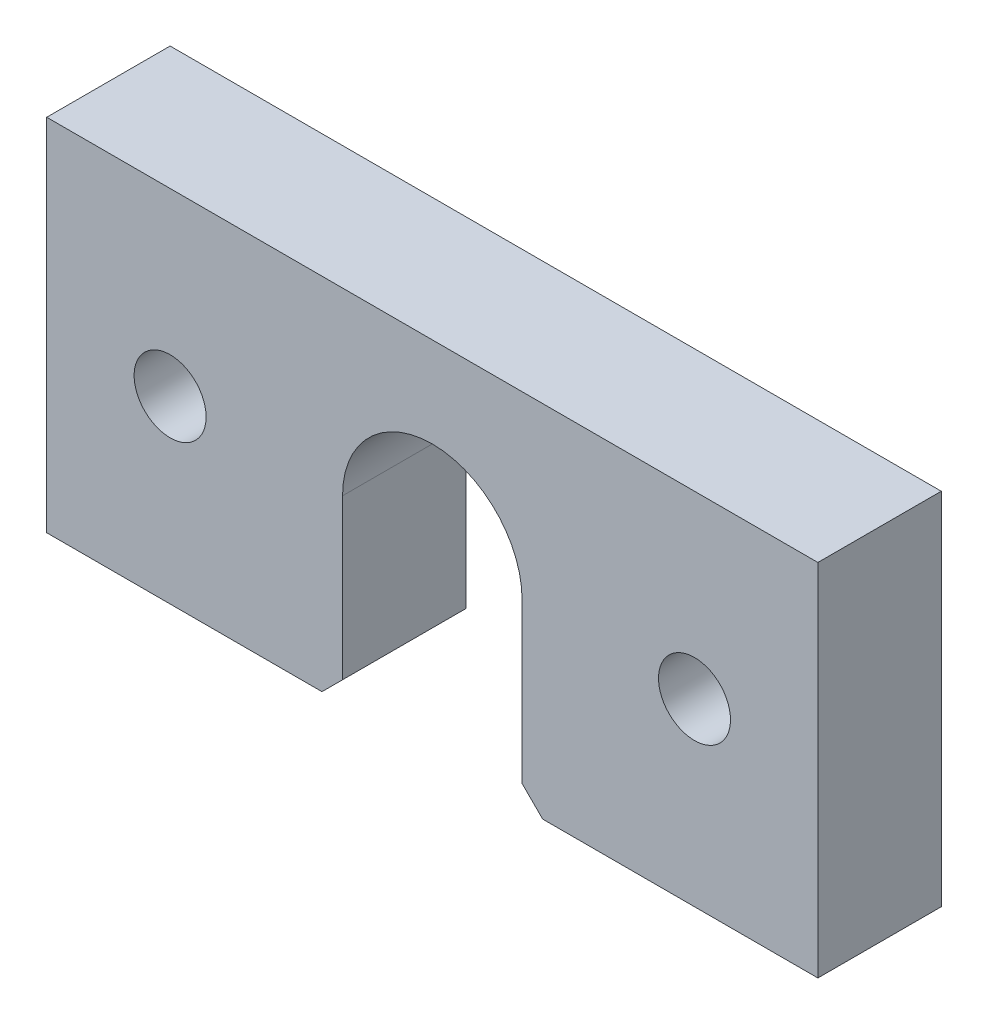
SolidWorks part; units mm, degrees
ref_plane "Front Plane" through (0, 0, 0) normal (0, 0, 1) x (1, 0, 0)
ref_plane "Top Plane" through (0, 0, 0) normal (0, 1, 0) x (1, 0, 0)
ref_plane "Right Plane" through (0, 0, 0) normal (1, 0, 0) x (0, 0, -1)
sketch "Sketch1" plane through (0, 0, 0) normal (0, 0, 1) x (1, 0, 0)
  line L1 (37.5, -17.5) -> (-37.5, -17.5)
  line L2 (37.5, -17.5) -> (37.5, 17.5)
  line L3 (37.5, 17.5) -> (-37.5, 17.5)
  line L4 (-37.5, -17.5) -> (-37.5, 17.5)
  line L5 (37.5, -17.5) -> (-37.5, 17.5) construction
  line L6 (37.5, 17.5) -> (-37.5, -17.5) construction
  point P0 (0, 0)
  dimension "D1" = 75
  dimension "D2" = 35
extrude "Boss-Extrude1" add sketch "Sketch1" along normal blind 12
sketch "Sketch2" plane through (0, 0, 0) normal (0, 0, -1) x (-1, 0, 0)
  line L0 (-8.7312, 0) -> (-8.7312, -17.5)
  line L1 (37.5, -17.5) -> (-37.5, -17.5) construction
  line L2 (8.7312, 0) -> (8.7312, -17.5)
  line L3 (37.5, 17.5) -> (37.5, -17.5) construction
  line L4 (-8.7312, -17.5) -> (8.7312, -17.5)
  arc A0 (8.7312, 0) -> (-8.7312, 0) centre (0, 0) ccw
  dimension "D1" = 17.4625
  dimension "D3" = 8.7688
  dimension "D4" = 28.7688
  dimension "D2" = 0
extrude "Cut-Extrude1" cut sketch "Sketch2" against normal up to next
hole_wizard "M8x1.0 Tapped Hole1" positions "Sketch5" profile "Sketch4" tap size "M8x1.0" standard "ANSI Metric" end condition through all
sketch "Sketch5" plane through (0, 0, 12) normal (0, 0, 1) x (1, 0, 0)
  line L0 (0, 0) -> (0, 8.7312) construction
  arc A0 (8.7312, 0) -> (-8.7312, 0) centre (0, 0) ccw construction
  point P0 (-25.5, 0)
  point P2 (25.5, 0)
  dimension "D1" = 51
sketch "Sketch4" plane through (-25.5, 0, 12) normal (1, 0, 0) x (0, -1, 0)
  line L0 (0, 0) -> (0, 12)
  line L1 (0, 12) -> (3.5, 12)
  line L2 (3.5, 12) -> (3.5, 0)
  line L5 (3.5, 0) -> (0, 0)
  line L11 (0, -6.35) -> (0, 107.95) construction
  dimension "Thru Tap Drill Dia." = 7
  dimension "Thru Tap Drill Depth" = 12
cosmetic thread "Hole Thread1" parameters "D2"=8
cosmetic thread "Hole Thread2" parameters "D2"=8
chamfer "Chamfer1" distance 2 angle 45 2 edges at (8.7312, -17.5, 6) (-8.7312, -17.5, 6)
